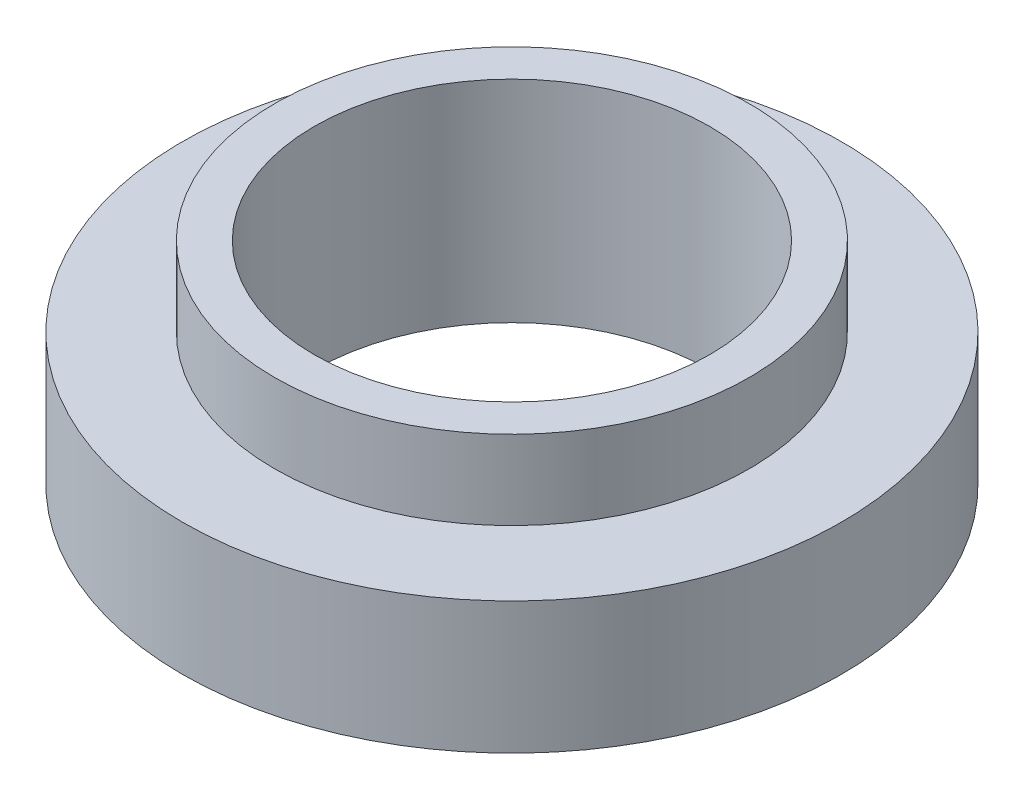
SolidWorks part; units mm, degrees
ref_plane "Front Plane" through (0, 0, 0) normal (0, 0, 1) x (1, 0, 0)
ref_plane "Top Plane" through (0, 0, 0) normal (0, 1, 0) x (1, 0, 0)
ref_plane "Right Plane" through (0, 0, 0) normal (1, 0, 0) x (0, 0, -1)
sketch "Sketch1" plane through (0, 0, 0) normal (0, 1, 0) x (1, 0, 0)
  circle A0 centre (0, 0) radius 12.5
  dimension "D1" = 25
extrude "Boss-Extrude1" add sketch "Sketch1" along normal blind 5
sketch "Sketch2" plane through (0, 5, 0) normal (0, 1, 0) x (1, 0, 0)
  circle A0 centre (0, 0) radius 9
  dimension "D1" = 18
extrude "Boss-Extrude2" add sketch "Sketch2" along normal blind 3
sketch "Sketch3" plane through (0, 8, 0) normal (0, 1, 0) x (1, 0, 0)
  circle A0 centre (0, 0) radius 7.5
  dimension "D1" = 15
extrude "Cut-Extrude1" cut sketch "Sketch3" against normal blind 13
